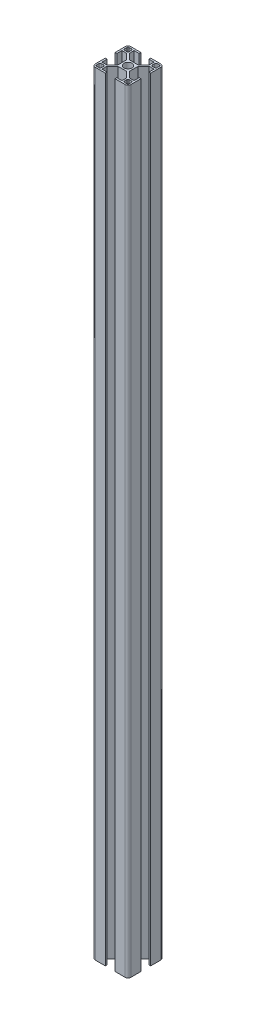
SolidWorks part; units mm, degrees
material "氧化铝"
ref_plane "前视基准面" through (0, 0, 0) normal (0, 0, 1) x (1, 0, 0)
ref_plane "上视基准面" through (0, 0, 0) normal (0, 1, 0) x (1, 0, 0)
ref_plane "右视基准面" through (0, 0, 0) normal (1, 0, 0) x (0, 0, -1)
other "Configuration Table"
sketch "草图1" plane through (0, 0, 0) normal (0, 1, 0) x (1, 0, 0)
  line L0 (-25.7983, 0) -> (25.4552, 0) construction
  line L1 (0, 19.6731) -> (0, -18.6486) construction
  line L2 (-4.1, 15) -> (-12.5, 15)
  line L3 (-15, 12.5) -> (-15, 4.1)
  line L4 (15, 12.5) -> (15, 4.1)
  line L5 (4.1, 15) -> (12.5, 15)
  line L6 (4.1, -15) -> (12.5, -15)
  line L7 (15, -12.5) -> (15, -4.1)
  line L8 (-15, -12.5) -> (-15, -4.1)
  line L9 (-4.1, -15) -> (-12.5, -15)
  line L10 (-13.5, 4.1) -> (-13.5, 8.4)
  line L11 (-8.4, 13.5) -> (-4.1, 13.5)
  line L12 (-3.6893, 4.75) -> (3.6893, 4.75)
  line L13 (-4.75, 3.6893) -> (-4.75, -3.6893)
  line L14 (-13.5, 8.4) -> (-9.4607, 8.4)
  line L15 (-9.4607, 8.4) -> (-4.75, 3.6893)
  line L16 (-22.4821, 22.4821) -> (22.6119, -22.6119) construction
  line L17 (-8.4, 9.4607) -> (-3.6893, 4.75)
  line L18 (-8.4, 13.5) -> (-8.4, 9.4607)
  line L19 (8.4, 13.5) -> (8.4, 9.4607)
  line L20 (13.5, 8.4) -> (9.4607, 8.4)
  line L21 (13.5, 4.1) -> (13.5, 8.4)
  line L22 (9.4607, 8.4) -> (4.75, 3.6893)
  line L23 (8.4, 9.4607) -> (3.6893, 4.75)
  line L24 (8.4, 13.5) -> (4.1, 13.5)
  line L25 (4.75, 3.6893) -> (4.75, -3.6893)
  line L26 (-4.1, 13.5) -> (-4.1, 15)
  line L27 (-13.5, 4.1) -> (-15, 4.1)
  line L28 (13.5, 4.1) -> (15, 4.1)
  line L29 (4.1, 15) -> (4.1, 13.5)
  line L30 (13.5, -4.1) -> (15, -4.1)
  line L31 (13.5, -4.1) -> (13.5, -8.4)
  line L32 (13.5, -8.4) -> (9.4607, -8.4)
  line L33 (8.4, -13.5) -> (8.4, -9.4607)
  line L34 (8.4, -13.5) -> (4.1, -13.5)
  line L35 (4.1, -15) -> (4.1, -13.5)
  line L36 (-4.1, -13.5) -> (-4.1, -15)
  line L37 (-8.4, -13.5) -> (-4.1, -13.5)
  line L38 (-8.4, -13.5) -> (-8.4, -9.4607)
  line L39 (9.4607, -8.4) -> (4.75, -3.6893)
  line L40 (8.4, -9.4607) -> (3.6893, -4.75)
  line L41 (-8.4, -9.4607) -> (-3.6893, -4.75)
  line L42 (-9.4607, -8.4) -> (-4.75, -3.6893)
  line L43 (-13.5, -8.4) -> (-9.4607, -8.4)
  line L44 (-13.5, -4.1) -> (-13.5, -8.4)
  line L45 (-13.5, -4.1) -> (-15, -4.1)
  line L46 (-3.6893, -4.75) -> (3.6893, -4.75)
  line L47 (-10.7, 13.7) -> (-12.7, 13.7)
  line L48 (-9.7, 12.7) -> (-9.7, 10.7)
  line L49 (-10.7, 9.7) -> (-12.7, 9.7)
  line L50 (-13.7, 10.7) -> (-13.7, 12.7)
  line L51 (13.7, 10.7) -> (13.7, 12.7)
  line L52 (10.7, 9.7) -> (12.7, 9.7)
  line L53 (9.7, 12.7) -> (9.7, 10.7)
  line L54 (10.7, 13.7) -> (12.7, 13.7)
  line L55 (10.7, -13.7) -> (12.7, -13.7)
  line L56 (9.7, -12.7) -> (9.7, -10.7)
  line L57 (10.7, -9.7) -> (12.7, -9.7)
  line L58 (13.7, -10.7) -> (13.7, -12.7)
  line L59 (-13.7, -10.7) -> (-13.7, -12.7)
  line L60 (-10.7, -9.7) -> (-12.7, -9.7)
  line L61 (-9.7, -12.7) -> (-9.7, -10.7)
  line L62 (-10.7, -13.7) -> (-12.7, -13.7)
  circle A0 centre (0, 0) radius 3.4
  arc A1 (-12.5, -15) -> (-15, -12.5) centre (-12.5, -12.5) cw
  arc A2 (12.5, -15) -> (15, -12.5) centre (12.5, -12.5) ccw
  arc A3 (12.5, 15) -> (15, 12.5) centre (12.5, 12.5) cw
  arc A4 (-12.5, 15) -> (-15, 12.5) centre (-12.5, 12.5) ccw
  arc A5 (-12.7, 13.7) -> (-13.7, 12.7) centre (-12.7, 12.7) ccw
  arc A6 (-13.7, 10.7) -> (-12.7, 9.7) centre (-12.7, 10.7) ccw
  arc A7 (-10.7, 9.7) -> (-9.7, 10.7) centre (-10.7, 10.7) ccw
  arc A8 (-10.7, 13.7) -> (-9.7, 12.7) centre (-10.7, 12.7) cw
  arc A9 (10.7, 13.7) -> (9.7, 12.7) centre (10.7, 12.7) ccw
  arc A10 (10.7, 9.7) -> (9.7, 10.7) centre (10.7, 10.7) cw
  arc A11 (13.7, 10.7) -> (12.7, 9.7) centre (12.7, 10.7) cw
  arc A12 (12.7, 13.7) -> (13.7, 12.7) centre (12.7, 12.7) cw
  arc A13 (12.7, -13.7) -> (13.7, -12.7) centre (12.7, -12.7) ccw
  arc A14 (13.7, -10.7) -> (12.7, -9.7) centre (12.7, -10.7) ccw
  arc A15 (10.7, -9.7) -> (9.7, -10.7) centre (10.7, -10.7) ccw
  arc A16 (10.7, -13.7) -> (9.7, -12.7) centre (10.7, -12.7) cw
  arc A17 (-10.7, -13.7) -> (-9.7, -12.7) centre (-10.7, -12.7) ccw
  arc A18 (-10.7, -9.7) -> (-9.7, -10.7) centre (-10.7, -10.7) cw
  arc A19 (-13.7, -10.7) -> (-12.7, -9.7) centre (-12.7, -10.7) cw
  arc A20 (-12.7, -13.7) -> (-13.7, -12.7) centre (-12.7, -12.7) cw
  dimension "D1" = 6.8
  dimension "D6" = 2.5
  dimension "D12" = 1
  dimension "D2" = 8.2
  dimension "D3" = 8.2
  dimension "D4" = 30
  dimension "D5" = 30
  dimension "D7" = 9.5
  dimension "D8" = 1.5
  dimension "D9" = 16.8
  dimension "D10" = 1.5
  dimension "D11" = 1.3
  dimension "D13" = 1.3
extrude "凸台-拉伸1" add sketch "草图1" along normal blind 650
